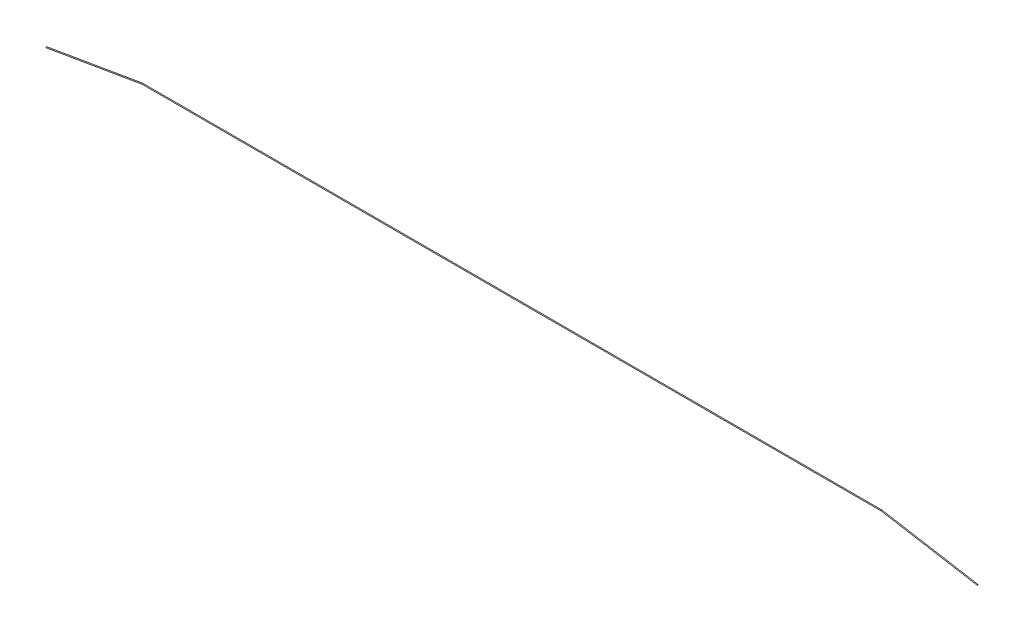
SolidWorks part; units mm, degrees
material "Plain Carbon Steel"
ref_plane "Front Plane" through (0, 0, 0) normal (0, 0, 1) x (1, 0, 0)
ref_plane "Top Plane" through (0, 0, 0) normal (0, 1, 0) x (1, 0, 0)
ref_plane "Right Plane" through (0, 0, 0) normal (1, 0, 0) x (0, 0, -1)
sketch "Sketch1" plane through (0, 0, 0) normal (0, 0, 1) x (1, 0, 0)
  line L0 (27.1899, 23.6141) -> (21.59, 24.5706)
  line L2 (21.59, 24.5706) -> (-21.59, 24.5706)
  line L3 (-21.59, 24.5706) -> (-27.1899, 23.6141)
  dimension "D1" = 43.18
sweep "Sweep1" add path "Sketch1" circular profile diameter 0.0508 parameters "D3"=0.0508
